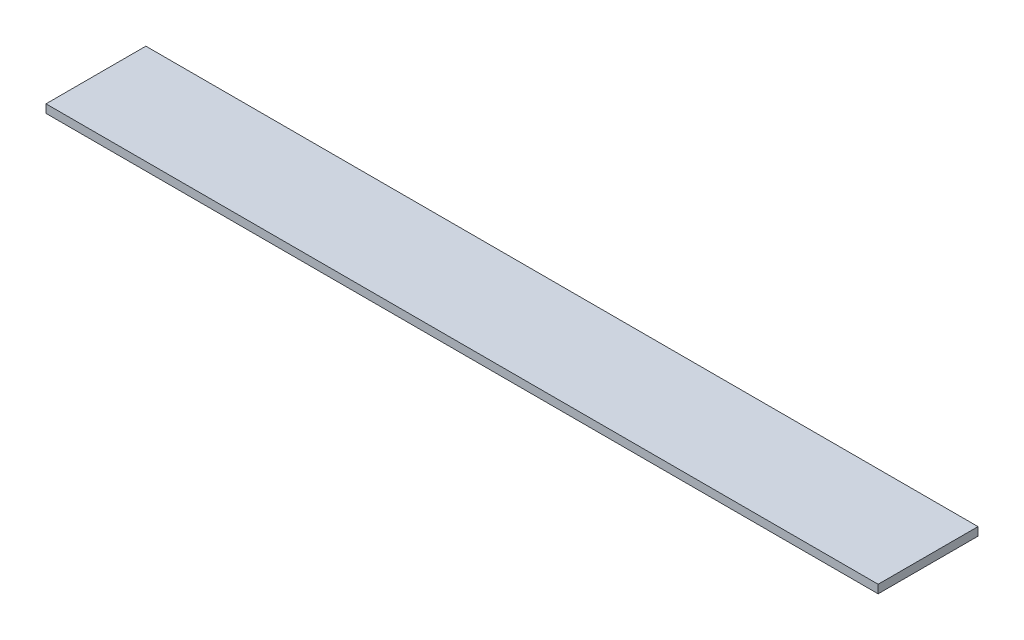
SolidWorks part; units mm, degrees
ref_plane "Alzado" through (0, 0, 0) normal (0, 0, 1) x (1, 0, 0)
ref_plane "Planta" through (0, 0, 0) normal (0, 1, 0) x (1, 0, 0)
ref_plane "Vista lateral" through (0, 0, 0) normal (1, 0, 0) x (0, 0, -1)
sketch "Croquis1" plane through (0, 0, 0) normal (0, 1, 0) x (1, 0, 0)
  line L1 (0, 0) -> (50, 0)
  line L2 (0, 0) -> (0, 6)
  line L3 (0, 6) -> (50, 6)
  line L4 (50, 0) -> (50, 6)
  dimension "D1" = 50
  dimension "D2" = 6
extrude "Saliente-Extruir1" add sketch "Croquis1" along normal blind 0.5
